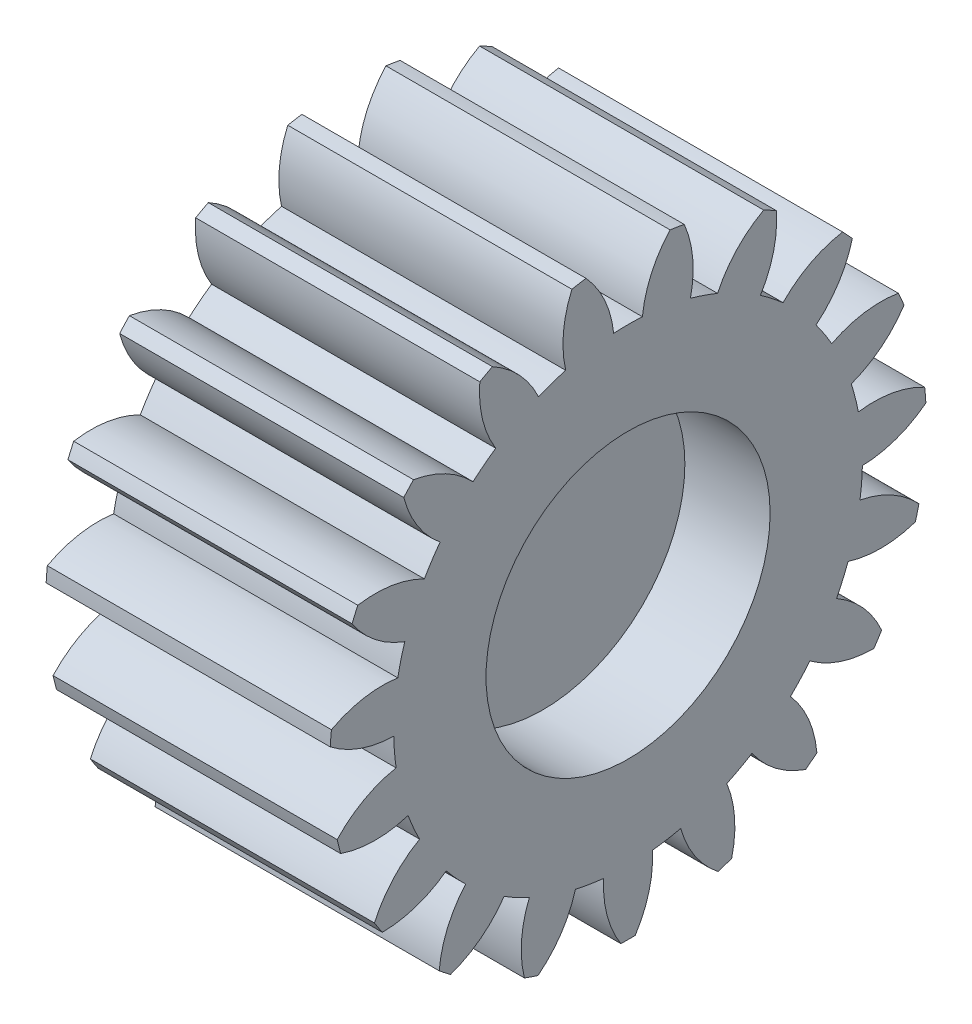
SolidWorks part; units mm, degrees
ref_plane "Plane1" through (0, 0, 0) normal (0, 0, 1) x (1, 0, 0)
ref_plane "Plane2" through (0, 0, 0) normal (0, 1, 0) x (1, 0, 0)
ref_plane "Plane3" through (0, 0, 0) normal (1, 0, 0) x (0, 0, -1)
other "Configuration Table"
sketch "HoldingSke" plane through (0, 0, 0) normal (0, 1, 0) x (1, 0, 0)
  line L0 (0, 0) -> (0.9455, -0.3256)
  line L1 (-15, 0) -> (100, 0) construction
  line L2 (0, 0) -> (-2.1039, 2.3779)
  line L3 (0, 0) -> (-11.863, 4.5341)
  line L4 (0, 0) -> (8.1655, 2.8116)
  line L5 (0, 0) -> (-46.8476, -17.4728)
  line L6 (0, 0) -> (-7.4607, -5.0337)
  line L7 (-2.1039, 2.3779) -> (8.6586, 51.2059)
  line L8 (-76.2, 54.61) -> (-75.3, 54.61)
  line L9 (-71.009, 38.7566) -> (-53.1078, 45.2721)
  line L10 (-76.2, 71.12) -> (104.1128, 71.12)
  line L11 (0, 0) -> (-9, 0)
  line L12 (-76.2, 101.6) -> (-76.162, 101.6)
  line L13 (24.9733, 27.94) -> (52.9518, 28.4284)
  line L14 (24.9733, 27.94) -> (24.9743, 27.94)
  line L15 (24.9733, 27.94) -> (100.4006, 29.5858)
  line L16 (-63.627, -1) -> (-12.827, -1)
  circle A0 centre (0, 0) radius 2.5
  circle A1 centre (0, 0) radius 8.249
  circle A2 centre (0, 0) radius 37.5
  circle A3 centre (0, 0) radius 2.5
  dimension "MHD" = 16.498
  dimension "Hub_dia" = 75
  dimension "Bore" = 5
  dimension "MBD" = 5
  dimension "Num_teeth" = 19
  dimension "Pitch" = 1
  dimension "Overall_len" = 50
  dimension "Show_teeth" = 19
  dimension "Thickness" = 9
  dimension "OAL" = 50.0001
  dimension "T_dim" = 0.9
  dimension "Ap" = 20
  dimension "H" = 19.05
  dimension "Pitch_radius" = 180.3128
  dimension "Width" = 9
  dimension "Backlash" = 0.038
  dimension "Addendum_fac" = 1
  dimension "Dedendum_fac" = 1.25
  dimension "Clearance_fac" = 0.25
  dimension "Dedendum_add" = 0.001
  dimension "Module" = 1
sketch "BasProSke" plane through (0, 0, 0) normal (0, 1, 0) x (1, 0, 0)
  line L0 (-10, 0) -> (60, 0) construction
  line L1 (0, 0) -> (0, 10.5)
  line L2 (0, 0) -> (12, 0)
  line L3 (12, 0) -> (12, 10.5)
  line L4 (12, 10.5) -> (0, 10.5)
  dimension "Thickness" = 12
  dimension "Diameter" = 21
revolve "Base-Revolve" add sketch "BasProSke" angle 360 about L0
sketch "TooCutSke" plane through (0, 0, 0) normal (1, 0, 0) x (0, 0, -1)
  line L1 (0, 0) -> (0, 107) construction
  line L2 (0, 0) -> (-0.851, 9.4618) construction
  line L3 (0, 0) -> (-3.1184, 18.6873) construction
  line L4 (-0.851, 9.4618) -> (-1.5592, 9.3436) construction
  arc A0 (0.505, 8.2335) -> (-0.505, 8.2335) centre (0, 0) ccw
  arc A1 (1.4994, 10.4181) -> (-1.4994, 10.4181) centre (0, 0) ccw
  circle A2 centre (0, 0) radius 9.5 construction
  circle A3 centre (0, 0) radius 8.9271 construction
  arc A4 (-0.505, 8.2335) -> (-1.4994, 10.4181) centre (-4.2838, 7.8321) ccw
  arc A5 (1.4994, 10.4181) -> (0.505, 8.2335) centre (4.2838, 7.8321) ccw
  dimension "Root_dia" = 16.498
  dimension "Overcut_dia" = 21.0508
  dimension "Pitch_dia" = 19
  dimension "Base_dia" = 17.8542
  dimension "Flank_rad" = 3.8
  dimension "Half_ang" = 9.474
  dimension "Half_CT" = 0.718
extrude "ToothCut" cut sketch "TooCutSke" along normal through all
fillet "Breaks" [suppressed] radius 0.02
fillet "RootFillets" [suppressed] radius 0.251
pattern_circular "TeethCuts" count 19 over 360 about axis through (0, 0, 0) along (1, 0, 0) of "ToothCut", "RootFillets", "Breaks"
sketch "HubNeaOneSke" plane through (0, 0, 0) normal (-1, 0, 0) x (0, 0, 1)
  circle A0 centre (0, 0) radius 8.249
  dimension "Diameter" = 16.498
extrude "HubNearOne" [suppressed] add sketch "HubNeaOneSke" along normal blind 38.0001
sketch "HubNeaBotSke" plane through (0, 0, 0) normal (-1, 0, 0) x (0, 0, 1)
  circle A0 centre (0, 0) radius 8.249
  dimension "Diameter" = 16.498
extrude "HubNearBoth" [suppressed] add sketch "HubNeaBotSke" along normal blind 19
ref_plane "FarPln" through (12, 0, 0) normal (1, 0, 0) x (0, 0, -1)
sketch "HubFarSke" plane through (12, 0, 0) normal (1, 0, 0) x (0, 0, -1)
  circle A0 centre (0, 0) radius 8.249
  dimension "Diameter" = 16.498
extrude "HubFar" [suppressed] add sketch "HubFarSke" along normal blind 19
sketch "BorSke" plane through (0, 0, 0) normal (1, 0, 0) x (0, 0, -1)
  circle A0 centre (0, 0) radius 2.5
  dimension "Diameter" = 5
extrude "Bore" cut sketch "BorSke" along normal mid plane 100.0001
sketch "KeySke" plane through (0, 0, 0) normal (1, 0, 0) x (0, 0, -1)
  line L0 (-1, 0) -> (-1, 3.4)
  line L1 (-1, 3.4) -> (1, 3.4)
  line L2 (1, 3.4) -> (1, 0)
  line L3 (0, 0) -> (0, 34) construction
  line L4 (-1, 0) -> (1, 0)
  dimension "Offset" = 3.4
  dimension "Width" = 2
extrude "Keyway" [suppressed] cut sketch "KeySke" along normal mid plane 100.0001
pattern_circular "Keyway2" [suppressed] count 2 every 90 about axis through (-10, 0, 0) along (1, 0, 0)
sketch "Sketch1" plane through (12, 0, 0) normal (1, 0, 0) x (0, 0, -1)
  circle A0 centre (0, 0) radius 5
  dimension "D1" = 10
extrude "Cut-Extrude1" cut sketch "Sketch1" against normal blind 3
sketch "Sketch2" plane through (9, 0, 0) normal (1, 0, 0) x (0, 0, -1)
  line L0 (-2.0854, 1.3788) -> (-2.0854, -1.3788)
  circle A0 centre (0, 0) radius 2.5
  circle M1 centre (0, 0) radius 2.5
extrude "Boss-Extrude1" add sketch "Sketch2" against normal up to surface (9 mm away) contours L0 M1
sketch "Sketch3" plane through (0, 0, 0) normal (-1, 0, 0) x (0, 0, 1)
  circle A0 centre (0, 0) radius 8.249
  circle A1 centre (0, 0) radius 10.5
extrude "Cut-Extrude2" cut sketch "Sketch3" against normal blind 2
sketch "Sketch4" plane through (0, 0, 0) normal (-1, 0, 0) x (0, 0, 1)
  circle A0 centre (0, 0) radius 8.249
extrude "Cut-Extrude3" cut sketch "Sketch4" against normal up to surface (2 mm away) up to face at (2, 6.3575, -6.9061)
sketch "Sketch5" plane through (2, 0, 0) normal (-1, 0, 0) x (0, 0, 1)
  circle A0 centre (0, 0) radius 2.5
extrude "Boss-Extrude3" add sketch "Sketch5" against normal up to surface (7 mm away) up to face at (9, 0, -0.2073)
equation "' \"Module@HoldingSke\" = 6.35"
equation "' \"Num_teeth@HoldingSke\" = 12"
equation "' \"Ap@HoldingSke\" =  20"
equation "' \"Ap@HoldingSke\" = 20"
equation "' \"Width@HoldingSke\" = 0.5 * 25.4"
equation "' \"Hub_dia@HoldingSke\"= 1 * 25.4"
equation "' \"Hub_dia@HoldingSke\" = 1 * 25.4"
equation "' \"Overall_len@HoldingSke\" = 1.0 * 25.4"
equation "' \"Bore@HoldingSke\" = 0.75 * 25.4"
equation "' \"T_dim@HoldingSke\" = 0.1 * 25.4"
equation "' \"Width@KeySke\" = 0.25 * 25.4"
equation "' \"Show_teeth@HoldingSke\" = 13"
equation "' \"Backlash@HoldingSke\" = 0.009 * 25.4"
equation "' \"Addendum_fac@HoldingSke\" = 1.0"
equation "' \"Dedendum_fac@HoldingSke\" = 1.25"
equation "' \"Dedendum_add@HoldingSke\" = 0.00005 * 25.4"
equation "' \"Clearance_fac@HoldingSke\" = 0.25"
equation "\"Pitch@HoldingSke\" = 1 / \"Module@HoldingSke\""
equation "\"Overcut_dia@TooCutSke\" = (\"Num_teeth@HoldingSke\" + 2 * \"Addendum_fac@HoldingSke\") / \"Pitch@HoldingSke\" + 0.002 * 25.4"
equation "\"Pitch_dia@TooCutSke\" = \"Num_teeth@HoldingSke\" / \"Pitch@HoldingSke\""
equation "\"Base_dia@TooCutSke\" = \"Num_teeth@HoldingSke\" / \"Pitch@HoldingSke\" * cos((\"Ap@HoldingSke\"  * 3.14159265 / 180))"
equation "\"Root_dia@TooCutSke\" = (\"Num_teeth@HoldingSke\" + 2) / \"Pitch@HoldingSke\" - 2 * (\"Addendum_fac@HoldingSke\" + \"Dedendum_fac@HoldingSke\") / \"Pitch@HoldingSke\" - \"Dedendum_add@HoldingSke\" * 2"
equation "\"Half_ang@TooCutSke\" = 180 / \"Num_teeth@HoldingSke\""
equation "\"Half_CT@TooCutSke\" = \"Num_teeth@HoldingSke\" / \"Pitch@HoldingSke\" * sin((3.14159265 / 2 / \"Num_teeth@HoldingSke\")) / 2 - 7 * \"Backlash@HoldingSke\" / 4"
equation "\"Flank_rad@TooCutSke\" = \"Num_teeth@HoldingSke\" / \"Pitch@HoldingSke\" / 5"
equation "\"Radius@RootFillets\" = \"Clearance_fac@HoldingSke\" / \"Pitch@HoldingSke\" + \"Dedendum_add@HoldingSke\""
equation "\"Break_rad@Breaks\" = 0.02 / \"Pitch@HoldingSke\""
equation "\"Thickness@HoldingSke\" = \"Width@HoldingSke\""
equation "\"OAL@HoldingSke\" = \"Thickness@HoldingSke\""
equation "\"MHD@HoldingSke\" = (\"Num_teeth@HoldingSke\" + 2) / \"Pitch@HoldingSke\" - 2 * (\"Addendum_fac@HoldingSke\" + \"Dedendum_fac@HoldingSke\")  / \"Pitch@HoldingSke\" - \"Dedendum_add@HoldingSke\" * 2"
equation "\"MBD@HoldingSke\" = (\"Num_teeth@HoldingSke\" + 2) / \"Pitch@HoldingSke\" - 2 * (\"Addendum_fac@HoldingSke\" + \"Dedendum_fac@HoldingSke\")  / \"Pitch@HoldingSke\" - \"Dedendum_add@HoldingSke\" * 2 - 0.002 * 25.4"
equation "\"MHD@HoldingSke\" = ((sgn( \"MHD@HoldingSke\" - \"Hub_dia@HoldingSke\" )-1)*( \"MHD@HoldingSke\" - \"Hub_dia@HoldingSke\" ))/-2+ \"Hub_dia@HoldingSke\""
equation "\"MBD@HoldingSke\" = ((sgn( \"MBD@HoldingSke\" - \"Bore@HoldingSke\" )-1)*( \"MBD@HoldingSke\" - \"Bore@HoldingSke\" ))/-2+ \"Bore@HoldingSke\""
equation "\"OAL@HoldingSke\" = ((sgn( \"OAL@HoldingSke\" - \"Overall_len@HoldingSke\" )+1)*( \"OAL@HoldingSke\" - \"Overall_len@HoldingSke\" ))/2 + \"Overall_len@HoldingSke\" + 0.000002 * 25.4"
equation "\"Num_teeth@TeethCuts\" = int( \"Show_teeth@HoldingSke\" ) + 1"
equation "\"Num_teeth@TeethCuts\" = ((sgn( \"Num_teeth@TeethCuts\" - \"Num_teeth@HoldingSke\" )-1)*( \"Num_teeth@TeethCuts\" - \"Num_teeth@HoldingSke\" ))/-2+ \"Num_teeth@HoldingSke\""
equation "\"Num_teeth@TeethCuts\" = ((sgn( \"Num_teeth@TeethCuts\" - 2.0)+1)*( \"Num_teeth@TeethCuts\" - 2.0))/2 +2.0"
equation "\"Angle@TeethCuts\" = 360.0 / \"Num_teeth@HoldingSke\""
equation "\"Diameter@BasProSke\" = (\"Num_teeth@HoldingSke\" + 2 * \"Addendum_fac@HoldingSke\") / \"Pitch@HoldingSke\""
equation "' \"Fillet_rad@BasProSke\" =  \"Thickness@HoldingSke\" * 0.05"
equation "' \"Fillet_rad@BasProSke\" = \"Thickness@HoldingSke\" * 0.05"
equation "\"MHD@HoldingSke\" = ((sgn( \"MHD@HoldingSke\" - \"Root_dia@TooCutSke\" )-1)*( \"MHD@HoldingSke\" - \"Root_dia@TooCutSke\" ))/-2+ \"Root_dia@TooCutSke\""
equation "\"Diameter@HubNeaOneSke\" = \"MHD@HoldingSke\""
equation "\"Length@HubNearOne\" = \"OAL@HoldingSke\" - \"Thickness@BasProSke\""
equation "\"Diameter@HubNeaBotSke\" = \"MHD@HoldingSke\""
equation "\"Length@HubNearBoth\" = ( \"OAL@HoldingSke\" - \"Thickness@BasProSke\" ) / 2.0"
equation "\"Thickness@FarPln\" = \"Thickness@BasProSke\""
equation "\"Diameter@HubFarSke\" = \"MHD@HoldingSke\""
equation "\"Length@HubFar\" = ( \"OAL@HoldingSke\" - \"Thickness@BasProSke\" ) / 2.0"
equation "\"Diameter@BorSke\" = \"MBD@HoldingSke\""
equation "\"D1@Bore\" = \"OAL@HoldingSke\" * 2.0"
equation "\"D1@Keyway\" = \"OAL@HoldingSke\" * 2.0"
equation "\"Offset@KeySke\" = \"T_dim@HoldingSke\" + \"MBD@HoldingSke\" / 2.0"
